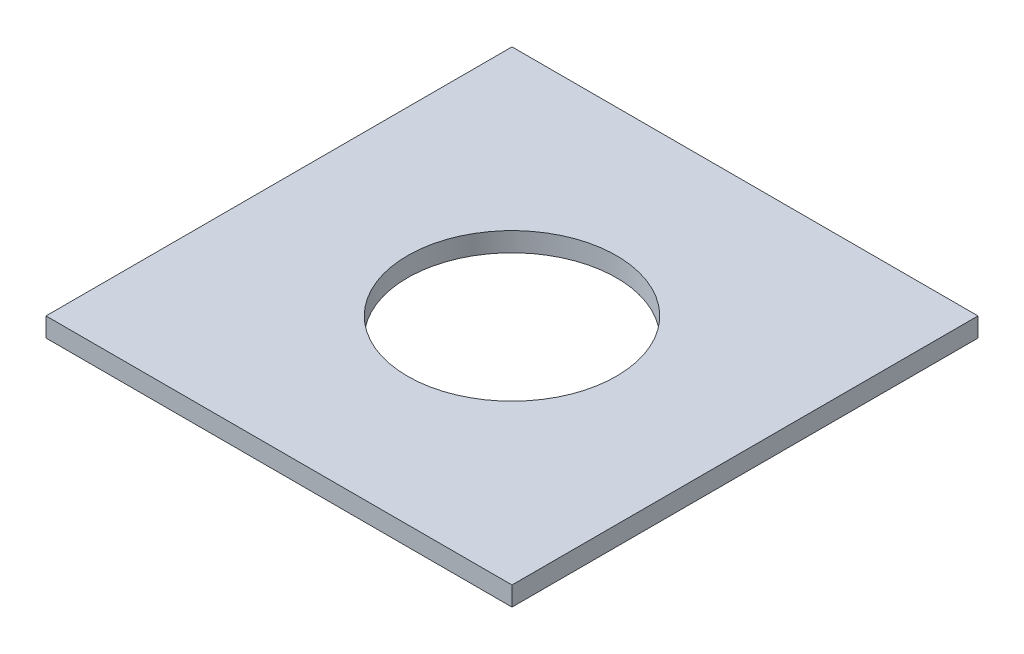
SolidWorks part; units mm, degrees
ref_plane "前视基准面" through (0, 0, 0) normal (0, 0, 1) x (1, 0, 0)
ref_plane "上视基准面" through (0, 0, 0) normal (0, 1, 0) x (1, 0, 0)
ref_plane "右视基准面" through (0, 0, 0) normal (1, 0, 0) x (0, 0, -1)
sketch "草图1" plane through (0, 0, 0) normal (0, 1, 0) x (1, 0, 0)
  line L0 (6.3333, 65) -> (6.3333, -129) construction
  line L1 (-90.6667, 65) -> (103.3333, 65)
  line L2 (-90.6667, 65) -> (-90.6667, -129)
  line L3 (-90.6667, -129) -> (103.3333, -129)
  line L4 (103.3333, 65) -> (103.3333, -129)
  line L5 (103.3333, -32) -> (-90.6667, -32) construction
  circle A0 centre (6.3333, -32) radius 43.5
  dimension "D3" = 87
  dimension "D1" = 194
  dimension "D2" = 194
extrude "凸台-拉伸1" add sketch "草图1" along normal blind 8
